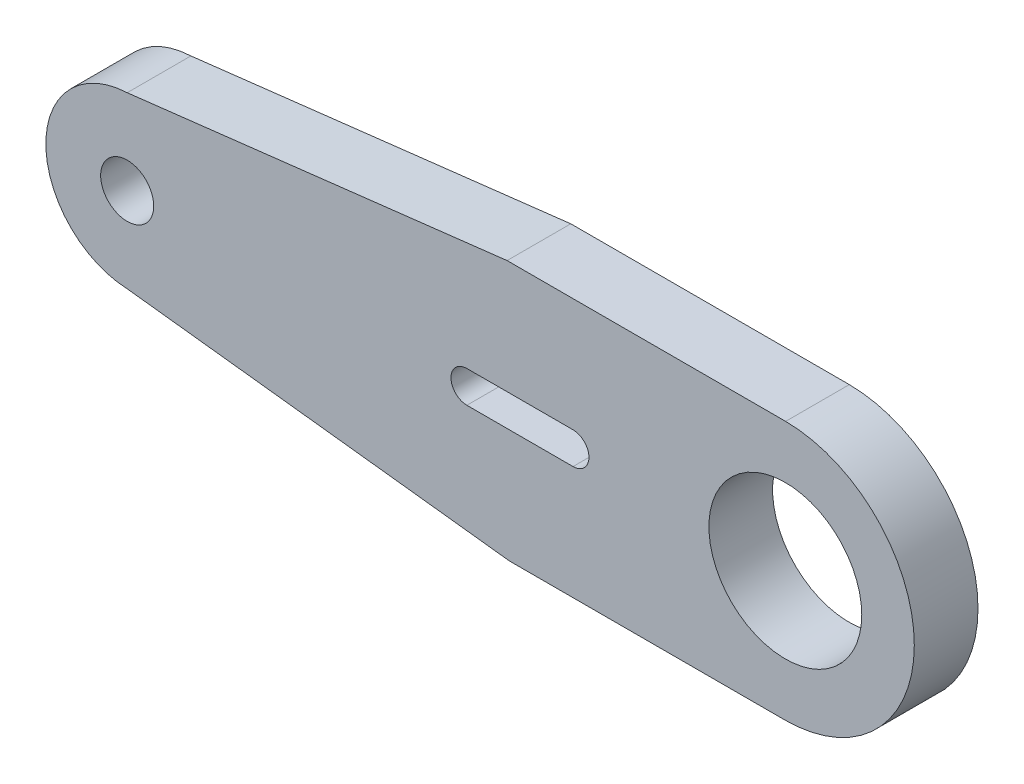
SolidWorks part; units mm, degrees
ref_plane "前基準面" through (0, 0, 0) normal (0, 0, 1) x (1, 0, 0)
ref_plane "上基準面" through (0, 0, 0) normal (0, 1, 0) x (1, 0, 0)
ref_plane "右基準面" through (0, 0, 0) normal (1, 0, 0) x (0, 0, -1)
sketch "草圖1" plane through (0, 0, 0) normal (0, 0, 1) x (1, 0, 0)
  line L0 (256.9249, 63.3369) -> (251.9249, 63.3369) construction
  line L1 (251.9249, 64.8369) -> (256.9249, 64.8369) construction
  line L2 (266.94, 70.1876) -> (253.8191, 70.1869) construction
  line L3 (235.925, 60.0869) -> (253.9249, 57.9869) construction
  line L4 (253.8191, 70.1869) -> (235.925, 68.0869) construction
  line L5 (256.9249, 63.3369) -> (251.9249, 63.3369)
  line L6 (251.9249, 64.8369) -> (256.9249, 64.8369)
  line L7 (266.94, 70.1876) -> (253.8191, 70.1869)
  line L8 (235.925, 60.0869) -> (253.9249, 57.9869)
  line L9 (253.8191, 70.1869) -> (235.925, 68.0869)
  line L10 (253.9249, 57.9869) -> (266.9249, 57.9869)
  circle A0 centre (235.925, 64.0869) radius 1.25 construction
  arc A1 (251.9249, 64.8369) -> (251.9249, 63.3369) centre (251.9249, 64.0869) ccw construction
  arc A2 (256.9249, 63.3369) -> (256.9249, 64.8369) centre (256.9249, 64.0869) ccw construction
  circle A3 centre (266.9249, 64.087) radius 3.6 construction
  arc A4 (235.925, 68.0869) -> (235.925, 60.0869) centre (236.0967, 64.0869) ccw construction
  circle A5 centre (235.925, 64.0869) radius 1.25
  arc A6 (251.9249, 64.8369) -> (251.9249, 63.3369) centre (251.9249, 64.0869) ccw
  arc A7 (256.9249, 63.3369) -> (256.9249, 64.8369) centre (256.9249, 64.0869) ccw
  circle A8 centre (266.9249, 64.087) radius 3.6
  arc A9 (235.925, 68.0869) -> (235.925, 60.0869) centre (236.0967, 64.0869) ccw
  arc A10 (266.9249, 57.9869) -> (266.94, 70.1876) centre (266.8998, 64.0873) ccw
extrude "填料-伸長1" add sketch "草圖1" along normal blind 3
